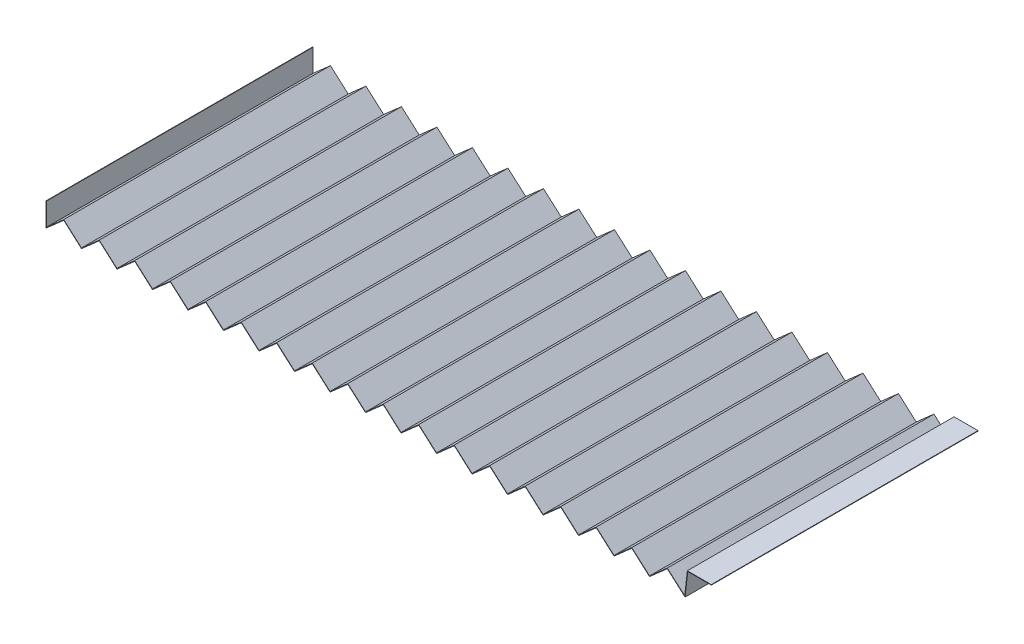
SolidWorks part; units mm, degrees
ref_plane "Front Plane" through (0, 0, 0) normal (0, 0, 1) x (1, 0, 0)
ref_plane "Top Plane" through (0, 0, 0) normal (0, 1, 0) x (1, 0, 0)
ref_plane "Right Plane" through (0, 0, 0) normal (1, 0, 0) x (0, 0, -1)
sketch "Sketch1" plane through (0, 0, 0) normal (0, 0, 1) x (1, 0, 0)
  line L0 (0, 0) -> (11.3156, 9.9983)
  line L1 (11.3156, 9.9983) -> (22.6312, 0)
  line L2 (0, 0) -> (511, 0) construction
  line L3 (22.6312, 0) -> (33.9469, 9.9983)
  line L4 (33.9469, 9.9983) -> (45.2625, 0)
  line L5 (45.2625, 0) -> (56.5781, 9.9983)
  line L6 (56.5781, 9.9983) -> (67.8937, 0)
  line L7 (67.8937, 0) -> (79.2094, 9.9983)
  line L8 (79.2094, 9.9983) -> (90.525, 0)
  line L9 (90.525, 0) -> (101.8406, 9.9983)
  line L10 (101.8406, 9.9983) -> (113.1562, 0)
  line L11 (113.1562, 0) -> (124.4719, 9.9983)
  line L12 (124.4719, 9.9983) -> (135.7875, 0)
  line L13 (135.7875, 0) -> (147.1031, 9.9983)
  line L14 (147.1031, 9.9983) -> (158.4187, 0)
  line L15 (158.4187, 0) -> (169.7344, 9.9983)
  line L16 (169.7344, 9.9983) -> (181.05, 0)
  line L17 (181.05, 0) -> (192.3656, 9.9983)
  line L18 (192.3656, 9.9983) -> (203.6812, 0)
  line L19 (0, 0) -> (0, 15.1)
  line L20 (203.6812, 0) -> (214.9968, 9.9983)
  line L21 (214.9968, 9.9983) -> (226.3125, 0)
  line L22 (226.3125, 0) -> (237.6281, 9.9983)
  line L23 (237.6281, 9.9983) -> (248.9437, 0)
  line L24 (248.9437, 0) -> (260.2593, 9.9983)
  line L25 (260.2593, 9.9983) -> (271.575, 0)
  line L26 (271.575, 0) -> (282.8906, 9.9983)
  line L27 (282.8906, 9.9983) -> (294.2062, 0)
  line L28 (294.2062, 0) -> (305.5218, 9.9983)
  line L29 (305.5218, 9.9983) -> (316.8375, 0)
  line L30 (316.8375, 0) -> (328.1531, 9.9983)
  line L31 (328.1531, 9.9983) -> (339.4687, 0)
  line L32 (339.4687, 0) -> (350.7843, 9.9983)
  line L33 (350.7843, 9.9983) -> (362.1, 0)
  line L34 (362.1, 0) -> (373.4156, 9.9983)
  line L35 (373.4156, 9.9983) -> (384.7312, 0)
  line L36 (384.7312, 0) -> (396.0468, 9.9983)
  line L37 (396.0468, 9.9983) -> (407.3625, 0)
  line L38 (407.3625, 0) -> (409.0974, 15)
  line L39 (409.0974, 15) -> (424.0974, 15)
  line L41 (426.0974, 13.6) -> (426.0974, 34.6) construction
  dimension "D1" = 511
  dimension "D2" = 15.1
  dimension "D3" = 15
  dimension "D4" = 22.6312
  dimension "D6" = 15
  dimension "D7" = 2
  dimension "D5" = 18
extrude "Extrude-Thin1" add sketch "Sketch1" along normal mid plane 170 thin thin type one direction reverse wall 0.3
